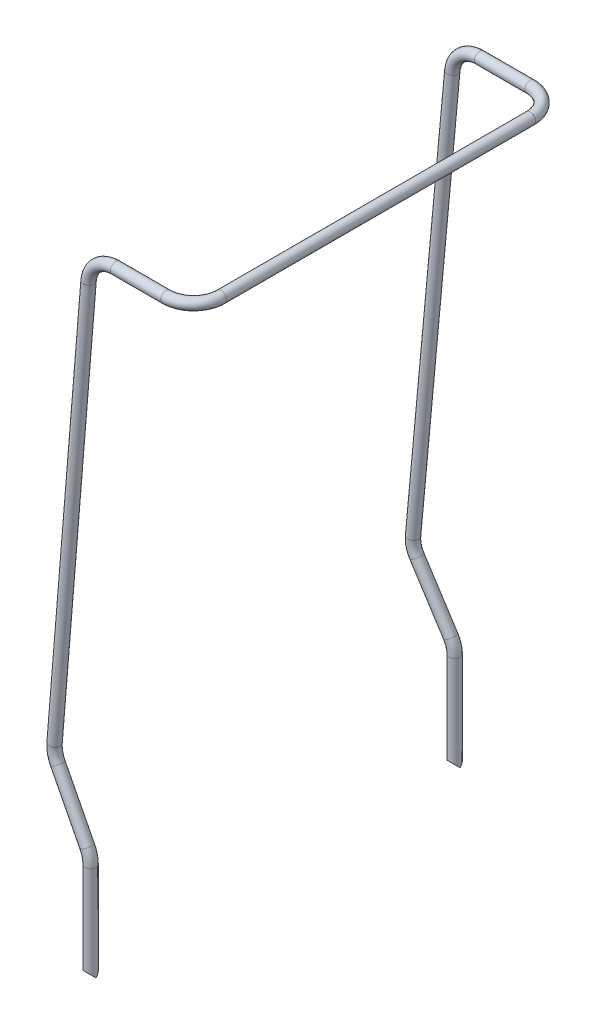
SolidWorks part; units mm, degrees
material "AISI 304"
ref_plane "Plano frontal" through (0, 0, 0) normal (0, 0, 1) x (1, 0, 0)
ref_plane "Plano superior" through (0, 0, 0) normal (0, 1, 0) x (1, 0, 0)
ref_plane "Plano direito" through (0, 0, 0) normal (1, 0, 0) x (0, 0, -1)
ref_plane "Plano1" through (0, 250, 0) normal (0, 1, 0) x (1, 0, 0)
ref_plane "Plano2" through (0, 800, 0) normal (0, 1, 0) x (1, 0, 0)
ref_plane "Plano3" through (0, 910, 0) normal (0, 1, 0) x (1, 0, 0)
sketch "Esboço1" plane through (0, 0, 0) normal (0, 1, 0) x (1, 0, 0)
  line L0 (0, 162.7552) -> (0, -162.7552) construction
  line L1 (0, 0) -> (910, 0) construction
  line L2 (910, 265) -> (910, -265) construction
  line L3 (37.1501, 202.6536) -> (910, 265) construction
  line L4 (37.1501, -202.6536) -> (910, -265) construction
  arc A0 (0, -162.7552) -> (37.1501, -202.6536) centre (40, -162.7552) ccw construction
  arc A1 (0, 162.7552) -> (37.1501, 202.6536) centre (40, 162.7552) cw construction
  point P9 (0, -200)
  point P12 (0, 200)
  dimension "D3" = 40
  dimension "D1" = 400
  dimension "D2" = 910
  dimension "D4" = 530
sketch "Esboço2" plane through (0, 250, 0) normal (0, 1, 0) x (1, 0, 0)
  line L0 (0, 162.7552) -> (0, -162.7552) construction
  line L1 (0, 0) -> (910, 0) construction
  line L2 (910, 265) -> (910, -265) construction
  line L3 (37.1501, 202.6536) -> (910, 265) construction
  line L4 (37.1501, -202.6536) -> (910, -265) construction
  arc A0 (0, -162.7552) -> (37.1501, -202.6536) centre (40, -162.7552) ccw construction
  arc A1 (0, 162.7552) -> (37.1501, 202.6536) centre (40, 162.7552) cw construction
  point P9 (0, -200)
  point P12 (0, 200)
  point P16 (802.8714, 257.348)
  dimension "D3" = 40
  dimension "D1" = 400
  dimension "D2" = 910
sketch "Esboço3" plane through (0, 800, 0) normal (0, 1, 0) x (1, 0, 0)
  line L0 (0, 162.7552) -> (0, -162.7552) construction
  line L1 (0, 0) -> (910, 0) construction
  line L2 (910, 265) -> (910, -265) construction
  line L3 (37.1501, 202.6536) -> (910, 265) construction
  line L4 (37.1501, -202.6536) -> (910, -265) construction
  arc A0 (0, -162.7552) -> (37.1501, -202.6536) centre (40, -162.7552) ccw construction
  arc A1 (0, 162.7552) -> (37.1501, 202.6536) centre (40, 162.7552) cw construction
  point P9 (0, -200)
  point P12 (0, 200)
  dimension "D3" = 40
  dimension "D1" = 400
  dimension "D2" = 910
sketch "Esboço4" plane through (0, 910, 0) normal (0, 1, 0) x (1, 0, 0)
  line L0 (0, 162.4326) -> (0, -163.0779) construction
  line L1 (0, 0) -> (910, 0) construction
  line L2 (910, 265) -> (910, -265) construction
  line L3 (37.1354, 202.3299) -> (910, 265) construction
  line L4 (37.1648, -202.9773) -> (910, -265) construction
  arc A0 (0, -163.0779) -> (37.1648, -202.9773) centre (40, -163.0779) ccw construction
  arc A1 (0, 162.4326) -> (37.1354, 202.3299) centre (40, 162.4326) cw construction
  point P9 (0, -200.3364)
  point P12 (0, 199.6636)
  dimension "D3" = 40
  dimension "D1" = 400
  dimension "D2" = 910
sketch3d "3DSketch1"
  line L0 (910, 0, 265) -> (910, 139.2691, 265)
  line L1 (904.6546, 159.2691, 264.6182) -> (858.6942, 239.0777, 261.3353)
  line L2 (37.1501, 250, 202.6536) -> (910, 250, 265) construction
  line L3 (853.5006, 262.564, 260.9643) -> (906.8129, 873.4781, 264.7723)
  line L4 (946.6614, 910, 265) -> (1020, 910, 265)
  line L5 (1060, 910, 225) -> (1060, 910, -225)
  line L6 (1020, 910, -265) -> (946.6614, 910, -265)
  line L7 (910, 0, -265) -> (910, 139.2691, -265)
  line L8 (37.1501, 0, -202.6536) -> (910, 0, -265) construction
  line L9 (904.6546, 159.2691, -264.6182) -> (858.6942, 239.0777, -261.3353)
  line L10 (37.1501, 250, -202.6536) -> (910, 250, -265) construction
  line L11 (853.5006, 262.564, -260.9643) -> (906.8129, 873.4781, -264.7723)
  line L12 (910, 0, -265) -> (910, 910, -265) construction
  line L13 (467.1121, 277.6413, 0) -> (1136.0767, 277.6413, 0) construction
  arc A0 (858.6942, 239.0777, 261.3353) -> (853.5006, 262.564, 260.9643) centre (893.2472, 259.0777, 263.8034) ccw
  arc A1 (910, 139.2691, 265) -> (904.6546, 159.2691, 264.6182) centre (870.1017, 139.2691, 262.1501) ccw
  arc A2 (858.6942, 239.0777, -261.3353) -> (853.5006, 262.564, -260.9643) centre (893.2472, 259.0777, -263.8034) ccw
  arc A3 (910, 139.2691, -265) -> (904.6546, 159.2691, -264.6182) centre (870.1017, 139.2691, -262.1501) ccw
  arc A4 (906.8129, 873.4781, 264.7723) -> (946.6614, 910, 265) centre (946.6614, 870.0008, 264.7507) ccw
  arc A5 (946.6614, 910, -265) -> (906.8129, 873.4781, -264.7723) centre (946.6614, 870.0008, -264.7507) ccw
  arc A6 (1060, 910, -225) -> (1020, 910, -265) centre (1020, 910, -225) ccw
  arc A7 (1020, 910, 265) -> (1060, 910, 225) centre (1020, 910, 225) ccw
  point P10 (852.4042, 250, 260.886)
  point P11 (896.097, 259.0777, 223.905)
  point P14 (910, 149.987, 265)
  point P15 (867.2518, 139.2691, 302.0485)
  point P32 (852.4042, 250, -260.886)
  point P33 (890.3973, 259.0777, -303.7017)
  point P36 (910, 149.987, -265)
  point P37 (872.9515, 139.2691, -222.2518)
  point P40 (910, 910, 265)
  point P41 (946.6614, 870.2501, 224.7514)
  point P44 (910, 910, -265)
  point P45 (946.6614, 870.2501, -224.7514)
  point P46 (1060, 910, -265)
  point P47 (1020, 950, -225)
  point P50 (1060, 910, 265)
  point P51 (1020, 950, 225)
  dimension "D3" = 40
  dimension "D6" = 40
  dimension "D8" = 40
  dimension "D9" = 40
  dimension "D1" = 150
  dimension "D2" = 145
  dimension "D4" = 150
  dimension "D5" = 145
  dimension "D7" = 150
other "Pipe - configured 21.3 X 2.3(5)"
ref_plane "Plano6" through (910, 0, 265) normal (0, 1, 0) x (1, 0, 0)
sketch "Sketch1" plane through (910, 0, 265) normal (0, 1, 0) x (1, 0, 0)
  circle A0 centre (0, 0) radius 6.4375
  circle A1 centre (0, 0) radius 7.9375
  point P3 (0, 0)
  dimension "Out_dia" = 15.875
  dimension "D1" = 1.5
sketch "Esboço12" plane through (0, 0, 0) normal (0, 0, 1) x (1, 0, 0)
  circle A0 centre (910, 0) radius 7.9375
extrude "Corte-extrusão3" cut sketch "Esboço12" against normal through all both and the other way through all
ref_plane "Plano7" through (910, 0, 0) normal (1, 0, 0) x (0, 0, -1)
sketch "Esboço14" plane through (910, 0, 0) normal (1, 0, 0) x (0, 0, -1)
  circle A0 centre (-265, 0) radius 7.9375
  circle A1 centre (265, 0) radius 7.9375
  dimension "D1" = 15.875
  dimension "D2" = 15.875
extrude "Corte-extrusão5" cut sketch "Esboço14" against normal blind 30
sketch3d "3DSketch2"
  line L0 (854.3898, 250, 261.0278) -> (854.3898, 250, -261.0278) construction
  line L1 (37.1501, 250, 202.6536) -> (910, 250, 265) construction
  line L2 (37.1501, 250, -202.6536) -> (910, 250, -265) construction
  line L3 (854.3898, 250, -261.0278) -> (0, 250, -200) construction
  line L4 (0, 250, -200) -> (0, 250, 200) construction
  line L5 (0, 250, 200) -> (854.3898, 250, 261.0278) construction
  arc A0 (858.6942, 239.0777, 261.3353) -> (853.5006, 262.564, 260.9643) centre (893.2472, 259.0777, 263.8034) ccw construction
  arc A1 (858.6942, 239.0777, -261.3353) -> (853.5006, 262.564, -260.9643) centre (893.2472, 259.0777, -263.8034) ccw construction
  point P10 (896.097, 259.0777, 223.905)
  point P15 (890.3973, 259.0777, -303.7017)
